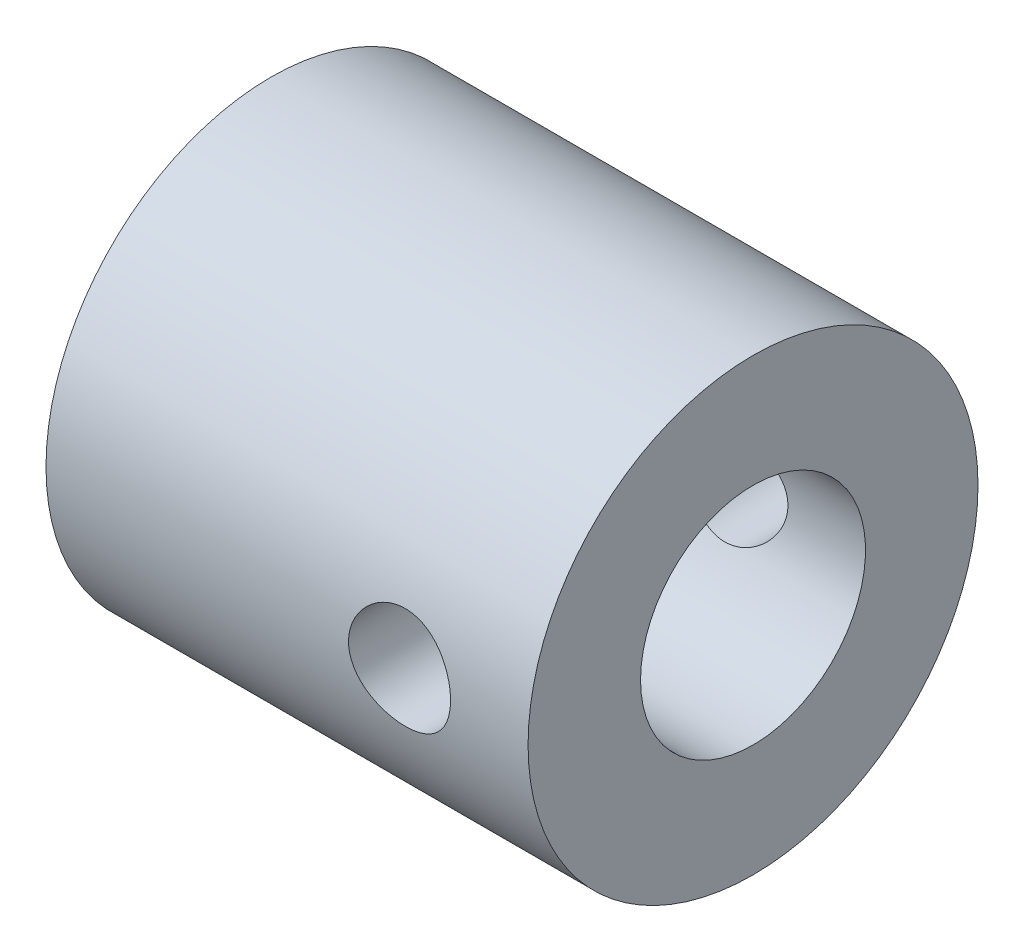
SolidWorks part; units mm, degrees
ref_plane "Front Plane" through (0, 0, 0) normal (0, 0, 1) x (1, 0, 0)
ref_plane "Top Plane" through (0, 0, 0) normal (0, 1, 0) x (1, 0, 0)
ref_plane "Right Plane" through (0, 0, 0) normal (1, 0, 0) x (0, 0, -1)
sketch "Sketch1" plane through (0, 0, 0) normal (0, 0, 1) x (1, 0, 0)
  line L0 (-11.7018, 0) -> (15.9187, 0) construction
  line L2 (0, 0) -> (7.5, 0)
  line L3 (0, 0) -> (0, 3.5)
  line L4 (0, 3.5) -> (7.5, 3.5)
  line L5 (7.5, 0) -> (7.5, 3.5)
  dimension "D1" = 3.5
  dimension "D2" = 7.5
revolve "Revolve1" add sketch "Sketch1" angle 360 about L0
sketch "Sketch3" plane through (0, 0, 0) normal (-1, 0, 0) x (0, 0, 1)
  circle A0 centre (0, 0) radius 1.75
sketch "Sketch8" plane through (0, 0, 0) normal (-1, 0, 0) x (0, 0, 1)
  circle A0 centre (0, 0) radius 1.75
extrude "Cut-Extrude6" cut sketch "Sketch8" against normal blind 10
cosmetic thread "Cosmetic Thread3" parameters "D2"=4
sketch "Sketch9" plane through (0, 0, 0) normal (0, 0, 1) x (1, 0, 0)
  line L0 (7.5, -3.5) -> (7.5, 3.5) construction
  circle A0 centre (5.5, 0) radius 0.7938
  dimension "D1" = 2
extrude "Cut-Extrude7" cut sketch "Sketch9" against normal through all both and the other way through all
